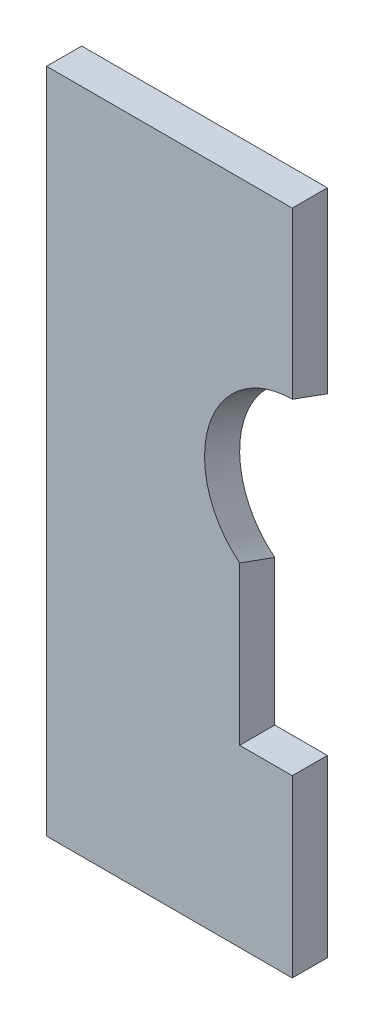
SolidWorks part; units mm, degrees
ref_plane "Plan de face" through (0, 0, 0) normal (0, 0, 1) x (1, 0, 0)
ref_plane "Plan de dessus" through (0, 0, 0) normal (0, 1, 0) x (1, 0, 0)
ref_plane "Plan de droite" through (0, 0, 0) normal (1, 0, 0) x (0, 0, -1)
sketch "Esquisse1" plane through (0, 0, 0) normal (0, 0, 1) x (1, 0, 0)
  line L1 (0, 0) -> (70, 0)
  line L2 (0, 0) -> (0, 190)
  line L3 (0, 190) -> (70, 190)
  line L4 (70, 0) -> (70, 190)
  point P7 (0, 0)
  dimension "D1" = 70
  dimension "D2" = 190
extrude "Boss.-Extru.1" add sketch "Esquisse1" along normal blind 10
ref_plane "Plan1" through (0, 0, 0) normal (0, -0.342, -0.9397) x (1, 0, 0)
sketch "Esquisse2" plane through (0, 0, 0) normal (0, -0.342, -0.9397) x (1, 0, 0)
  line L0 (70, 0) -> (70, -178.5416) construction
  line L1 (70, 3.4202) -> (70, 0) construction
  line L2 (70, -80.7785) -> (70, -130.7785)
  line L3 (70, -178.5416) -> (0, -178.5416) construction
  arc A0 (70, -130.7785) -> (70, -80.7785) centre (70, -105.7785) cw
  point P0 (70, -105.7785)
  dimension "D2" = 25
  dimension "D1" = 72.7631
extrude "Enlèv. mat.-Extru.1" cut sketch "Esquisse2" against normal through all
sketch "Esquisse3" plane through (0, 0, 0) normal (0, 0, -1) x (-1, 0, 0)
  line L0 (-70, 0) -> (-70, 85.9627) construction
  line L1 (-70, 49.9233) -> (-55, 49.9233)
  line L2 (-70, 49.9233) -> (-70, 94.9233)
  line L3 (-70, 94.9233) -> (-55, 94.9233)
  line L4 (-55, 49.9233) -> (-55, 94.9233)
  ellipse E0 centre (-70, 116.2068) end of major axis (-70, 89.6024) minor radius 25 (-70, 89.6024) -> (-70, 142.8113) ccw construction
  dimension "D1" = 45
  dimension "D2" = 15
extrude "Enlèv. mat.-Extru.2" cut sketch "Esquisse3" against normal through all
